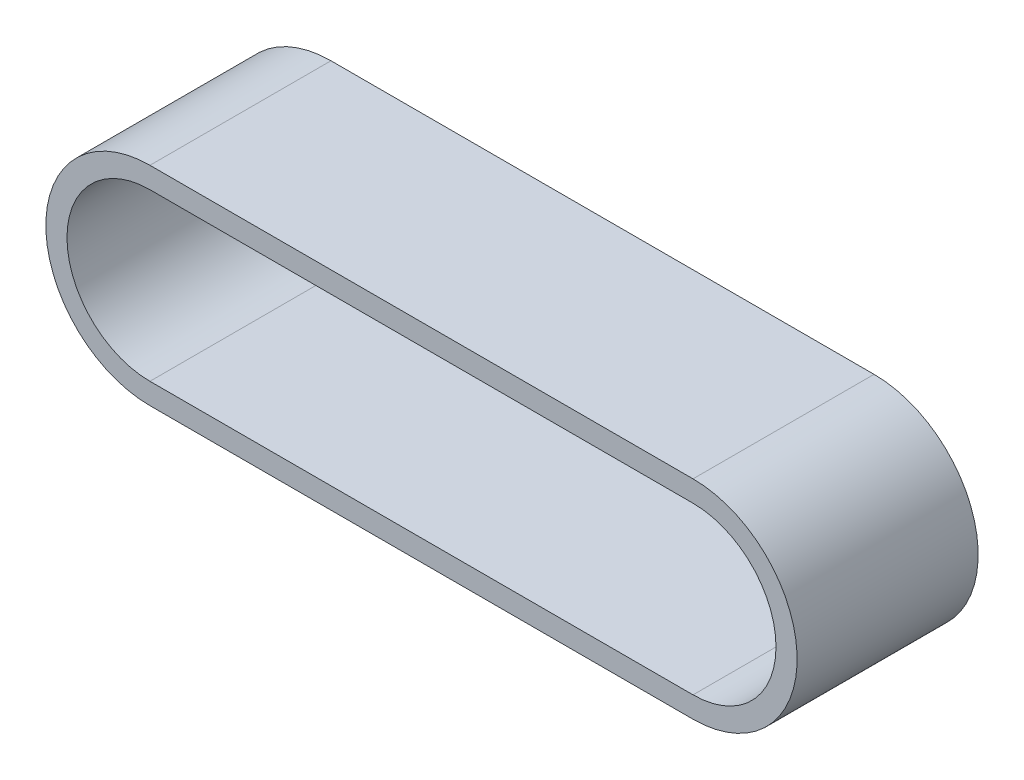
SolidWorks part; units mm, degrees
material "acero"
ref_plane "Alzado" through (0, 0, 0) normal (0, 0, 1) x (1, 0, 0)
ref_plane "Planta" through (0, 0, 0) normal (0, 1, 0) x (1, 0, 0)
ref_plane "Vista lateral" through (0, 0, 0) normal (1, 0, 0) x (0, 0, -1)
sketch "Croquis1" plane through (0, 0, 0) normal (0, 0, 1) x (1, 0, 0)
  line L0 (0, 0) -> (36, 0) construction
  line L1 (0, 5.5) -> (36, 5.5)
  line L2 (0, -5.5) -> (36, -5.5)
  line L3 (0, 6.9) -> (36, 6.9)
  line L4 (0, -6.9) -> (36, -6.9)
  arc A0 (0, 5.5) -> (0, -5.5) centre (0, 0) ccw
  arc A1 (36, -5.5) -> (36, 5.5) centre (36, 0) ccw
  arc A2 (36, -6.9) -> (36, 6.9) centre (36, 0) ccw
  arc A3 (0, 6.9) -> (0, -6.9) centre (0, 0) ccw
  point P3 (18, 0)
  dimension "D2" = 5.5
  dimension "D1" = 36
  dimension "D3" = 1.4
extrude "Saliente-Extruir1" add sketch "Croquis1" along normal blind 12
